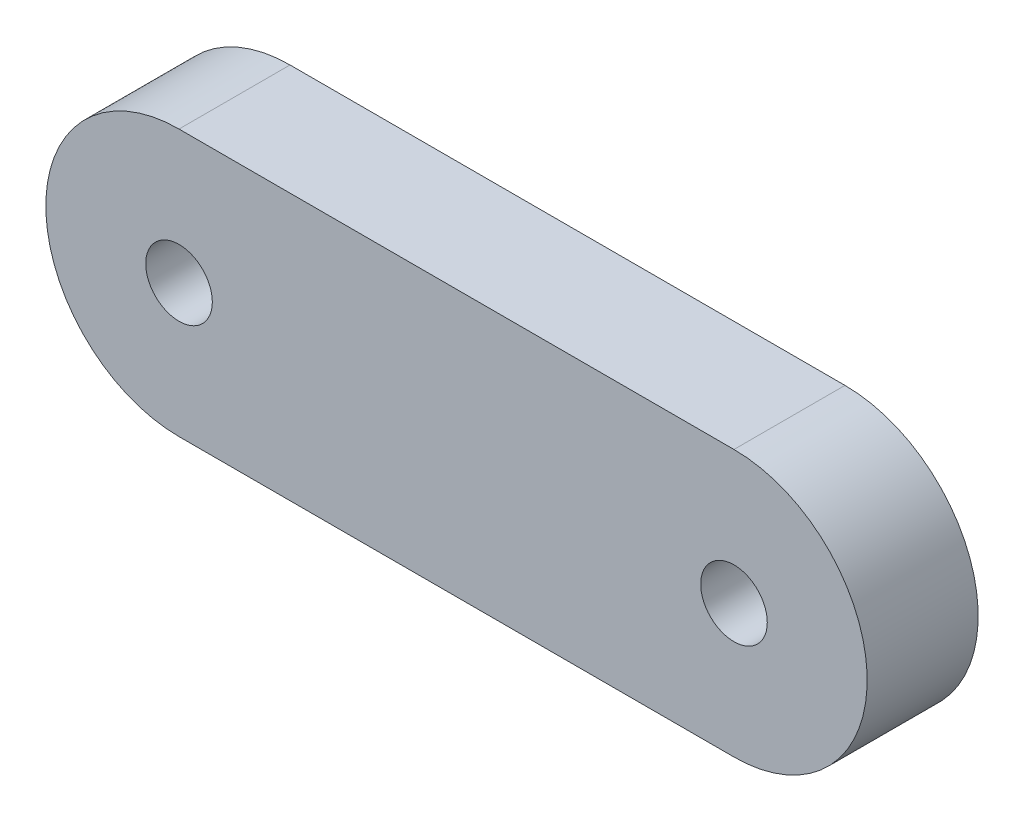
SolidWorks part; units mm, degrees
ref_plane "Plan de face" through (0, 0, 0) normal (0, 0, 1) x (1, 0, 0)
ref_plane "Plan de dessus" through (0, 0, 0) normal (0, 1, 0) x (1, 0, 0)
ref_plane "Plan de droite" through (0, 0, 0) normal (1, 0, 0) x (0, 0, -1)
sketch "Esquisse1" plane through (0, 0, 0) normal (0, 0, 1) x (1, 0, 0)
  line L0 (0, 0) -> (25, 0) construction
  line L1 (0, 6) -> (25, 6)
  line L2 (0, -6) -> (25, -6)
  arc A0 (0, 6) -> (0, -6) centre (0, 0) ccw
  arc A1 (25, -6) -> (25, 6) centre (25, 0) ccw
  circle A2 centre (25, 0) radius 1.5
  circle A3 centre (0, 0) radius 1.5
  point P3 (12.5, 0)
  dimension "D1" = 3
  dimension "D2" = 6
  dimension "D3" = 25
extrude "Boss.-Extru.1" add sketch "Esquisse1" along normal blind 5
